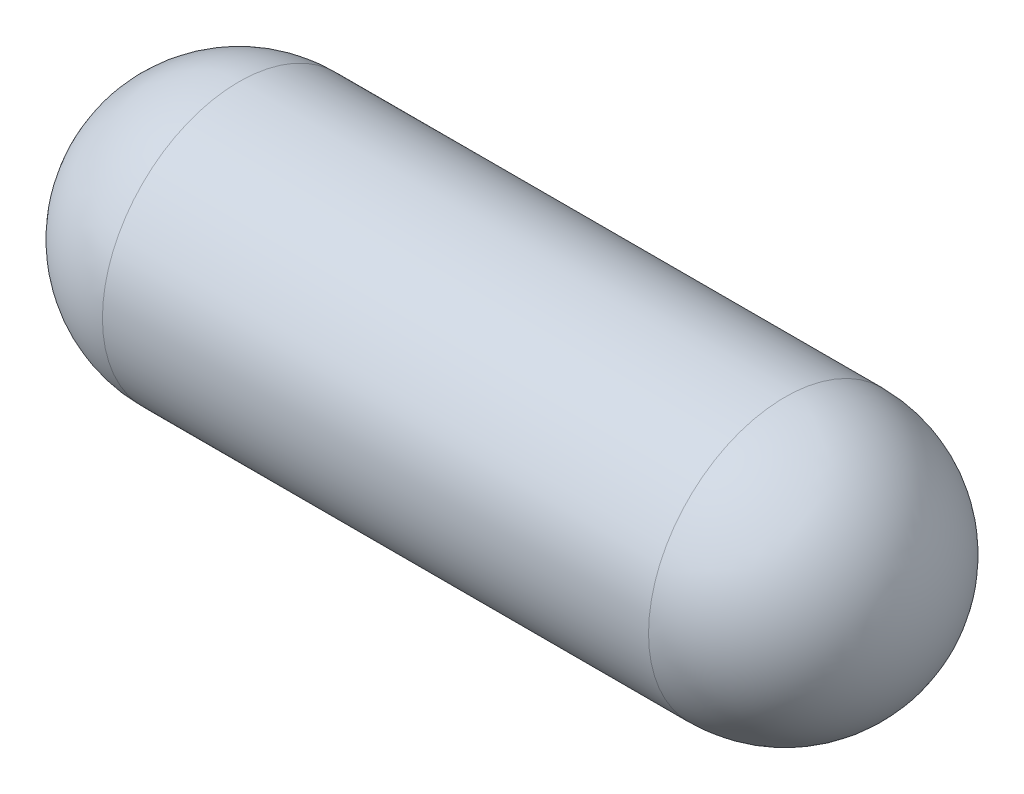
SolidWorks part; units mm, degrees
material "Acrylic (Medium-high impact)"
ref_plane "Front Plane" through (0, 0, 0) normal (0, 0, 1) x (1, 0, 0)
ref_plane "Top Plane" through (0, 0, 0) normal (0, 1, 0) x (1, 0, 0)
ref_plane "Right Plane" through (0, 0, 0) normal (1, 0, 0) x (0, 0, -1)
sketch "Sketch1" plane through (0, 0, 0) normal (0, 0, 1) x (1, 0, 0)
  line L0 (-14.0842, 0) -> (18.6113, 0) construction
  line L1 (0, 11.0033) -> (0, -9.5571) construction
  line L2 (3.175, 1.5875) -> (-3.175, 1.5875)
  line L3 (4.7625, 0) -> (-4.7625, 0)
  arc A0 (3.175, 1.5875) -> (4.7625, 0) centre (3.175, 0) cw
  arc A1 (-3.175, 1.5875) -> (-4.7625, 0) centre (-3.175, 0) ccw
  point P10 (0, 1.5875)
  dimension "D2" = 3.175
  dimension "D1" = 1.5875
revolve "Revolve1" add sketch "Sketch1" angle 360 about L0
